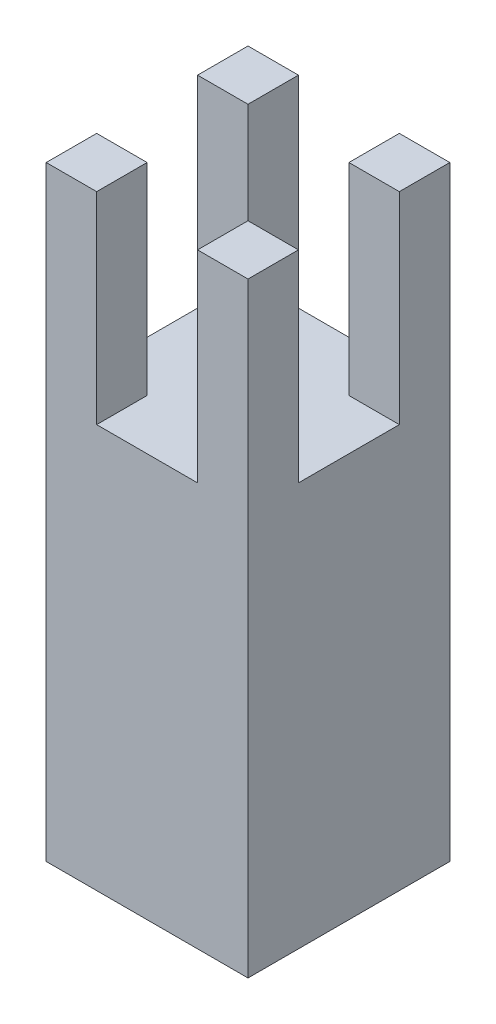
SolidWorks part; units mm, degrees
ref_plane "Front Plane" through (0, 0, 0) normal (0, 0, 1) x (1, 0, 0)
ref_plane "Top Plane" through (0, 0, 0) normal (0, 1, 0) x (1, 0, 0)
ref_plane "Right Plane" through (0, 0, 0) normal (1, 0, 0) x (0, 0, -1)
sketch "Sketch1" plane through (0, 0, 0) normal (0, 1, 0) x (1, 0, 0)
  line L1 (-50.8, -50.8) -> (50.8, -50.8)
  line L2 (-50.8, -50.8) -> (-50.8, 50.8)
  line L3 (-50.8, 50.8) -> (50.8, 50.8)
  line L4 (50.8, -50.8) -> (50.8, 50.8)
  line L5 (-50.8, -50.8) -> (50.8, 50.8) construction
  line L6 (-50.8, 50.8) -> (50.8, -50.8) construction
  point P0 (0, 0)
  dimension "D1" = 101.6
  dimension "D2" = 101.6
extrude "Boss-Extrude1" add sketch "Sketch1" along normal blind 304.8
sketch "Sketch2" plane through (0, 304.8, 0) normal (0, 1, 0) x (1, 0, 0)
  line L17 (50.8, 50.8) -> (-50.8, 50.8) construction
  line L18 (-25.4, -50.8) -> (25.4, -50.8)
  line L19 (-25.4, -50.8) -> (-25.4, 50.8)
  line L20 (-25.4, 50.8) -> (25.4, 50.8)
  line L21 (25.4, -50.8) -> (25.4, 50.8)
  line L22 (-25.4, -50.8) -> (25.4, 50.8) construction
  line L23 (-25.4, 50.8) -> (25.4, -50.8) construction
  line L24 (50.8, -50.8) -> (50.8, 50.8) construction
  line L25 (-50.8, -25.4) -> (50.8, -25.4)
  line L26 (-50.8, -25.4) -> (-50.8, 25.4)
  line L27 (-50.8, 25.4) -> (50.8, 25.4)
  line L28 (50.8, -25.4) -> (50.8, 25.4)
  line L29 (-50.8, -25.4) -> (50.8, 25.4) construction
  line L30 (-50.8, 25.4) -> (50.8, -25.4) construction
  point P0 (0, 0)
  point P7 (0, 0)
  line M7 (50.8, -50.8) -> (50.8, 50.8)
  line M8 (50.8, 50.8) -> (-50.8, 50.8)
  line M10 (-50.8, -50.8) -> (50.8, -50.8)
  dimension "D1" = 50.8
  dimension "D2" = 50.8
extrude "Cut-Extrude3" cut sketch "Sketch2" against normal blind 101.6 contours L25 L19 L21 M10 | L27 L21 L25 M7 | L27 L19 L25 L21 | L19 L27 L21 M8
